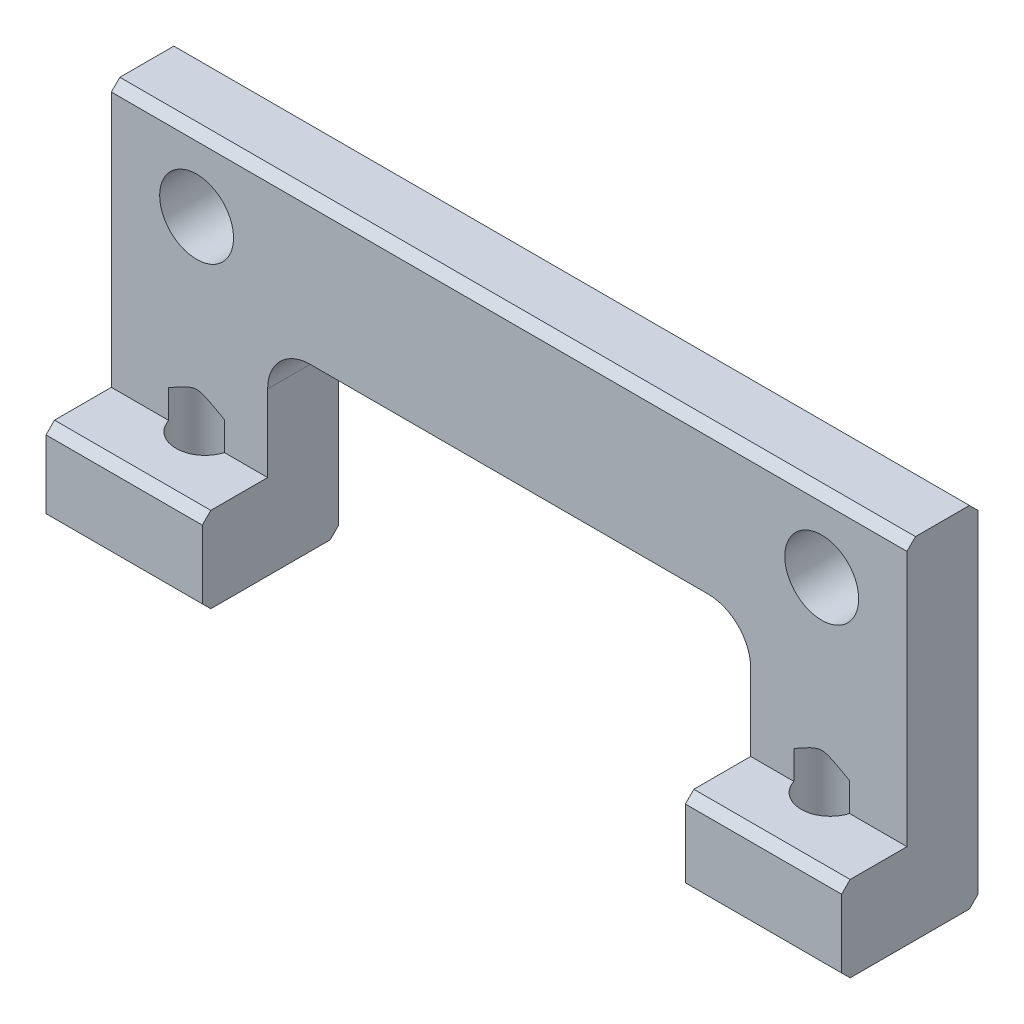
SolidWorks part; units mm, degrees
ref_plane "Front Plane" through (0, 0, 0) normal (0, 0, 1) x (1, 0, 0)
ref_plane "Top Plane" through (0, 0, 0) normal (0, 1, 0) x (1, 0, 0)
ref_plane "Right Plane" through (0, 0, 0) normal (1, 0, 0) x (0, 0, -1)
ref_plane "Plane1" through (0, 0, -2.5) normal (0, 0, -1) x (-1, 0, 0)
sketch "Sketch1" plane through (0, 0, -2.5) normal (0, 0, -1) x (-1, 0, 0)
  line L0 (-8.5, 0) -> (-8.5, 12.3)
  line L1 (-8.5, 12.3) -> (-14, 12.3)
  line L2 (-14, 12.3) -> (-14, 0)
  line L3 (-14, 0) -> (-8.5, 0)
extrude "Boss-Extrude1" add sketch "Sketch1" against normal blind 4.8
sketch "Sketch2" plane through (8.5, 0, 0) normal (-1, 0, 0) x (0, 0, 1)
  line L0 (2.3, 12.3) -> (0, 12.3)
  line L1 (0, 12.3) -> (0, 3)
  line L2 (0, 3) -> (2.3, 3)
  line L3 (2.3, 3) -> (2.3, 12.3)
extrude "Cut-Extrude1" cut sketch "Sketch2" against normal through all
sketch "Sketch3" plane through (8.5, 0, 0) normal (-1, 0, 0) x (0, 0, 1)
  line L0 (0, 7.2) -> (-2.5, 7.2)
  line L1 (-2.5, 7.2) -> (-2.5, 12.3)
  line L2 (-2.5, 12.3) -> (0, 12.3)
  line L3 (0, 12.3) -> (0, 7.2)
extrude "Boss-Extrude2" add sketch "Sketch3" along normal blind 22.5
sketch "Sketch4" plane through (0, 7.2, 0) normal (0, -1, 0) x (1, 0, 0)
  line L0 (-8.5, 0) -> (-8.5, -2.5)
  line L1 (-8.5, -2.5) -> (-14, -2.5)
  line L2 (-14, -2.5) -> (-14, 0)
  line L3 (-14, 0) -> (-8.5, 0)
extrude "Boss-Extrude3" add sketch "Sketch4" along normal blind 7.2
sketch "Sketch5" plane through (0, 0, 0) normal (0, 0, 1) x (1, 0, 0)
  line L0 (-14, 0) -> (-14, 3)
  line L1 (-14, 3) -> (-8.5, 3)
  line L2 (-8.5, 3) -> (-8.5, 0)
  line L3 (-8.5, 0) -> (-14, 0)
extrude "Boss-Extrude4" add sketch "Sketch5" along normal blind 2.3
hole_wizard "Ø2.6 (2.6) Diameter Hole1" positions "Sketch7" profile "Sketch6" hole size "Ø2.6" standard "ANSI Metric"
sketch "Sketch7" plane through (0, 0, -2.5) normal (0, 0, -1) x (-1, 0, 0)
  point P0 (11, 9.7)
  point P1 (-11, 9.7)
sketch "Sketch6" plane through (-11, 9.7, -2.5) normal (1, 0, 0) x (0, 1, 0)
  line L0 (0, 0) -> (0, 4.8)
  line L1 (0, 4.8) -> (1.3, 4.8)
  line L2 (1.3, 4.8) -> (1.3, 0)
  line L5 (1.3, 0) -> (0, 0)
  line L11 (0, -6.35) -> (0, 107.95) construction
  dimension "Thru Hole Dia." = 2.6
  dimension "Thru Hole Depth" = 4.8
hole_wizard "Ø2.05 (2.05) Diameter Hole1" positions "Sketch9" profile "Sketch8" hole size "Ø2.05" standard "ANSI Metric"
sketch "Sketch9" plane through (0, 0, 0) normal (0, -1, 0) x (-1, 0, 0)
  point P0 (-11, 0.3)
  point P1 (11, 0.3)
sketch "Sketch8" plane through (11, 0, -0.3) normal (1, 0, 0) x (0, 0, -1)
  line L0 (0, 0) -> (0, 4.6159)
  line L1 (0, 4.6159) -> (1.025, 4)
  line L2 (1.025, 4) -> (1.025, 0)
  line L5 (1.025, 0) -> (0, 0)
  line L10 (0, 4.6159) -> (-1.025, 4) construction
  line L11 (0, -6.35) -> (0, 107.95) construction
  dimension "Hole Dia." = 2.05
  dimension "Hole Depth" = 4
  dimension "Drill Angle" = 118
chamfer "Chamfer1" distance 0.3 angle 45 11 edges at (11.25, 0, -2.5) (-11.25, 0, -2.5) (11, 0, -1.325) (0, 12.3, 0) (0, 12.3, -2.5) (-11, 0, -1.325) (9.7, 9.7, -2.5) (11.25, 0, 2.3) (-11.25, 0, 2.3) (11.25, 3, 2.3) (-11.25, 3, 2.3)
chamfer "Chamfer2" distance 0.2 angle 45 1 edges at (-12.3, 9.7, -2.5)
fillet "Fillet1" radius 1.5 2 edges at (-8.5, 7.2, -1.25) (8.5, 7.2, -1.25)
